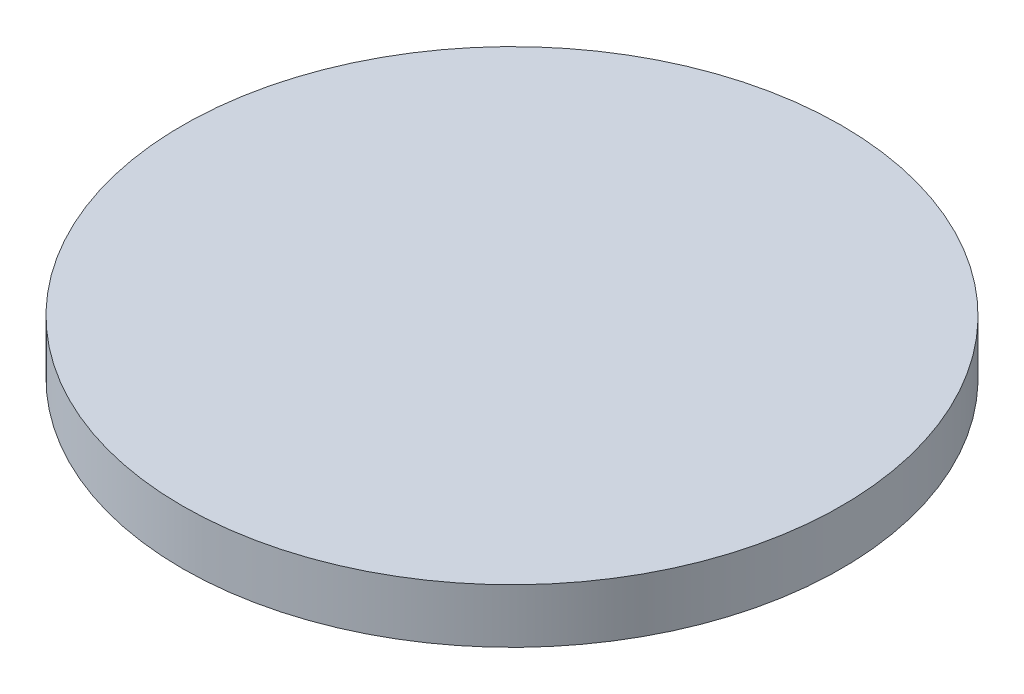
SolidWorks part; units mm, degrees
ref_plane "Front Plane" through (0, 0, 0) normal (0, 0, 1) x (1, 0, 0)
ref_plane "Top Plane" through (0, 0, 0) normal (0, 1, 0) x (1, 0, 0)
ref_plane "Right Plane" through (0, 0, 0) normal (1, 0, 0) x (0, 0, -1)
sketch "Sketch1" plane through (0, 0, 0) normal (0, 1, 0) x (1, 0, 0)
  circle A0 centre (0, 0) radius 243
  dimension "D1" = 486
extrude "Boss-Extrude1" add sketch "Sketch1" along normal blind 40 contours A0
shell "Shell1" thickness 10
